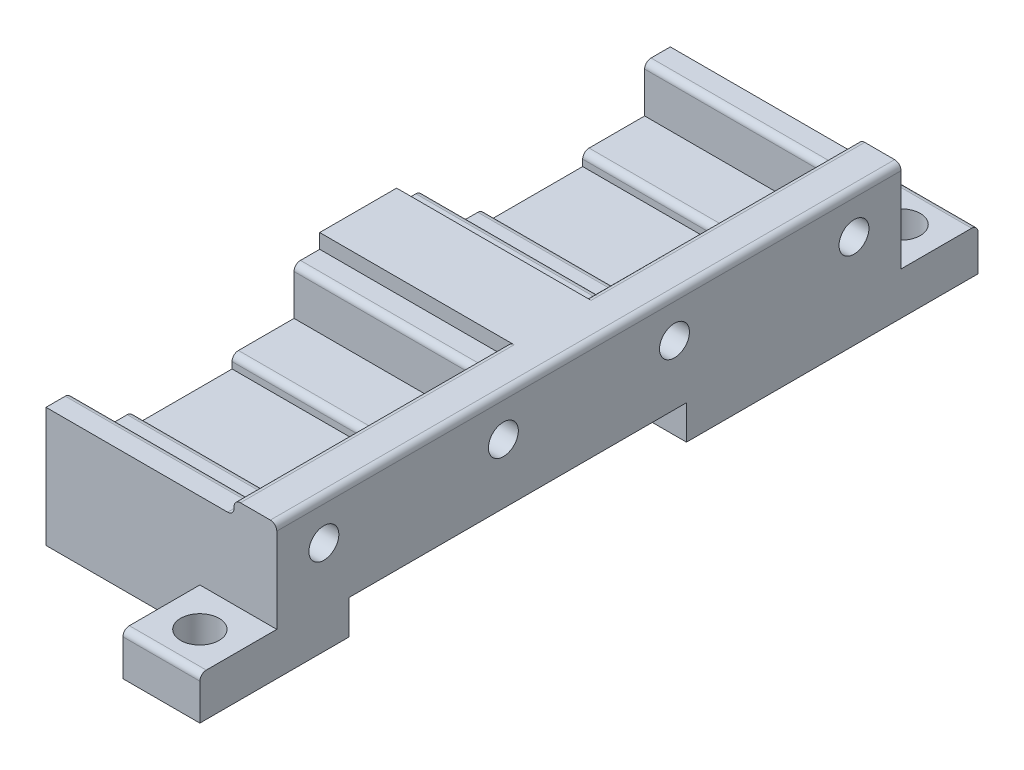
SolidWorks part; units mm, degrees
ref_plane "Front" through (0, 0, 0) normal (0, 0, 1) x (1, 0, 0)
ref_plane "Top" through (0, 0, 0) normal (0, 1, 0) x (1, 0, 0)
ref_plane "Right" through (0, 0, 0) normal (1, 0, 0) x (0, 0, -1)
sketch "Sketch1" plane through (0, 0, 0) normal (1, 0, 0) x (0, 0, -1)
  line L0 (-13.0089, 0) -> (13.0089, 0)
  line L1 (13.0089, 0) -> (13.0089, 8.5)
  line L2 (13.0089, 8.5) -> (5.7589, 8.5)
  line L3 (5.7589, 8.5) -> (5.7589, 7)
  line L4 (5.7589, 7) -> (-5.7589, 7)
  line L5 (-5.7589, 7) -> (-5.7589, 8.5)
  line L6 (-5.7589, 8.5) -> (-13.0089, 8.5)
  line L7 (-13.0089, 8.5) -> (-13.0089, 0)
  dimension "D1" = 8.5
  dimension "D2" = 7.25
  dimension "D3" = 26.0178
  dimension "D4" = 1.5
extrude "Boss-Extrude1" add sketch "Sketch1" along normal mid plane 22
sketch "Sketch3" plane through (0, 0, 0) normal (0, -1, 0) x (1, 0, 0)
  line L1 (-11, -13.0089) -> (11, -13.0089)
  line L2 (-11, -13.0089) -> (-11, -16.0089)
  line L3 (-11, -16.0089) -> (11, -16.0089)
  line L4 (11, -13.0089) -> (11, -16.0089)
  line L5 (-11, 13.0089) -> (11, 13.0089)
  line L6 (-11, 13.0089) -> (-11, 16.0089)
  line L7 (-11, 16.0089) -> (11, 16.0089)
  line L8 (11, 13.0089) -> (11, 16.0089)
  dimension "D1" = 3
  dimension "D2" = 22
  dimension "D3" = 3
  dimension "D4" = 22
extrude "Boss-Extrude2" add sketch "Sketch3" against normal blind 14
sketch "Sketch4" plane through (11, 0, 0) normal (1, 0, 0) x (0, 0, -1)
  line L0 (0, 0) -> (0, 15.7) construction
  line L1 (-16.0089, 0) -> (16.0089, 0) construction
  line L2 (-8.8, 15.7) -> (-16.0089, 15.7)
  line L3 (-16.0089, 14) -> (-16.0089, 0) construction
  line L4 (-16.0089, 15.7) -> (-16.0089, 0)
  line L5 (-16.0089, 0) -> (16.0089, 0)
  line L6 (16.0089, 0) -> (16.0089, 15.7)
  line L7 (16.0089, 14) -> (16.0089, 0) construction
  line L8 (16.0089, 15.7) -> (-8.8, 15.7)
  dimension "D2" = 15.7
extrude "Boss-Extrude3" add sketch "Sketch4" along normal blind 5
sketch "Sketch5" plane through (16, 0, 0) normal (1, 0, 0) x (0, 0, -1)
  line L0 (-16.0089, 11) -> (-10.5, 11) construction
  line L1 (-16.0089, 15.7) -> (-16.0089, 0) construction
  line L2 (-10.5, 11) -> (-10.5, 0) construction
  line L3 (-16.0089, 0) -> (16.0089, 0) construction
  line L4 (0, 0) -> (0, 15.7) construction
  line L5 (16.0089, 15.7) -> (-16.0089, 15.7) construction
  circle A0 centre (-10.5, 11) radius 1.75
  circle A1 centre (10.5, 11) radius 1.75
  dimension "D3" = 3.5
  dimension "D1" = 5.5089
  dimension "D2" = 11
extrude "Cut-Extrude1" cut sketch "Sketch5" against normal through all
sketch "Sketch6" plane through (0, 0, 0) normal (0, -1, 0) x (1, 0, 0)
  line L15 (16, 16.0089) -> (7, 16.0089)
  line L20 (16, 16.0089) -> (16, 25.0089)
  line L21 (16, 25.0089) -> (7, 25.0089)
  line L22 (7, 16.0089) -> (7, 25.0089)
  dimension "D3" = 9
  dimension "D4" = 9
extrude "Boss-Extrude4" add sketch "Sketch6" against normal blind 5
sketch "Sketch10" plane through (0, 0, 0) normal (0, -1, 0) x (1, 0, 0)
  line L0 (7, 20.5089) -> (16, 20.5089) construction
  line L1 (7, 25.0089) -> (7, 16.0089) construction
  line L2 (16, 25.0089) -> (16, -16.0089) construction
  line L3 (11.5, 25.0089) -> (11.5, 20.5089) construction
  line L4 (16, 25.0089) -> (7, 25.0089) construction
  circle A0 centre (11.5, 20.5089) radius 2.25
  dimension "D1" = 4.5
extrude "Cut-Extrude2" cut sketch "Sketch10" against normal through all
sketch "Sketch8" plane through (0, 0, -16.0089) normal (0, 0, -1) x (-1, 0, 0)
  line L1 (11, 0) -> (-16, 0)
  line L2 (11, 0) -> (11, 15.7)
  line L3 (11, 15.7) -> (-16, 15.7)
  line L4 (-16, 0) -> (-16, 15.7)
extrude "Boss-Extrude5" add sketch "Sketch8" along normal blind 4.5
fillet "Fillet1" radius 0.75 11 edges at (11.5, 5, 25.0089) (0, 8.5, 5.7589) (0, 8.5, -5.7589) (11, 11.25, 13.0089) (11, 11.25, -13.0089) (0, 14, 13.0089) (0, 14, -13.0089) (11, 15.7, 0) (11, 14, 14.5089) (11, 14, -14.5089) (16, 15.7, -2.25)
mirror "Mirror6" about plane through (0, 0, -20.5089) normal (0, 0, -1) of bodies 133
sketch "Sketch11" plane through (0, 0, 0) normal (0, -1, 0) x (1, 0, 0)
  line L0 (16, 25.0089) -> (16, -12.1711) construction
  line L2 (16, 25.0089) -> (16, -66.0267) construction
  line L3 (16, -12.1711) -> (0.65, -12.1711) construction
  line L4 (0.65, 7.5789) -> (16, 7.5789)
  line L5 (16, 7.5789) -> (16, -31.9211)
  line L6 (16, -31.9211) -> (-11, -31.9211)
  line L7 (-11, 16.0089) -> (-11, -57.0267) construction
  line L8 (-11, -31.9211) -> (-11, 7.5789)
  line L9 (-11, 7.5789) -> (0.65, 7.5789)
  circle A0 centre (0.65, -12.1711) radius 19.75 construction
  dimension "D3" = 39.5
  dimension "D1" = 37.18
  dimension "D2" = 15.35
extrude "Cut-Extrude3" cut sketch "Sketch11" against normal blind 4
sketch "Sketch12" plane through (0, 4, 0) normal (0, -1, 0) x (1, 0, 0)
  circle A0 centre (0.65, -12.1711) radius 1.5
  dimension "D1" = 3
extrude "Cut-Extrude4" cut sketch "Sketch12" against normal blind 2
